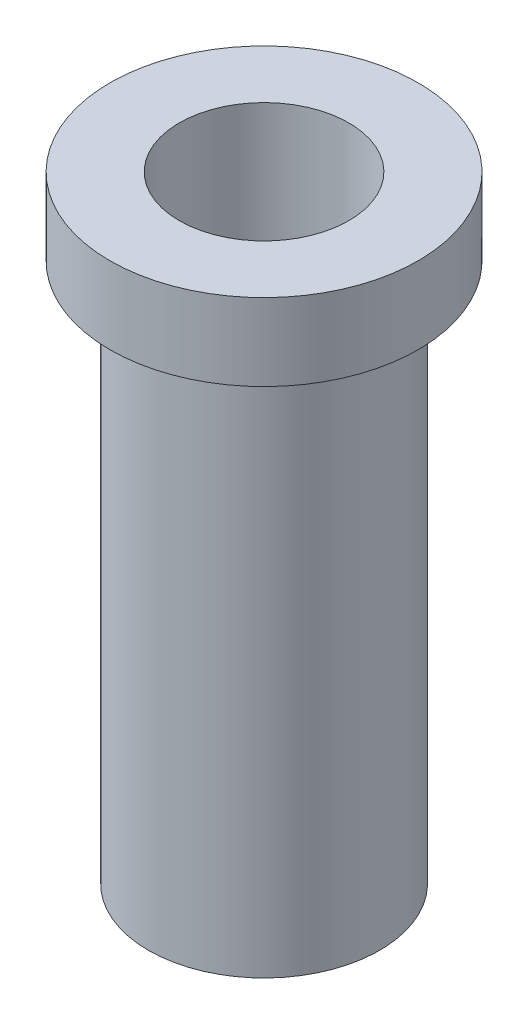
SolidWorks part; units mm, degrees
ref_plane "Front Plane" through (0, 0, 0) normal (0, 0, 1) x (1, 0, 0)
ref_plane "Top Plane" through (0, 0, 0) normal (0, 1, 0) x (1, 0, 0)
ref_plane "Right Plane" through (0, 0, 0) normal (1, 0, 0) x (0, 0, -1)
sketch "Sketch2" plane through (0, 0, 0) normal (0, 1, 0) x (1, 0, 0)
  circle A1 centre (0, 0) radius 7.5
  dimension "D2" = 15
extrude "Boss-Extrude4" add sketch "Sketch2" against normal blind 40 contours A1
sketch "Sketch5" plane through (0, 0, 0) normal (0, 1, 0) x (1, 0, 0)
  circle A0 centre (0, 0) radius 10
  dimension "D1" = 20
extrude "Boss-Extrude5" add sketch "Sketch5" against normal blind 5
sketch "Sketch6" plane through (0, 0, 0) normal (0, 1, 0) x (1, 0, 0)
  circle A0 centre (0, 0) radius 5.5
  dimension "D1" = 11
extrude "Cut-Extrude2" cut sketch "Sketch6" against normal through all
